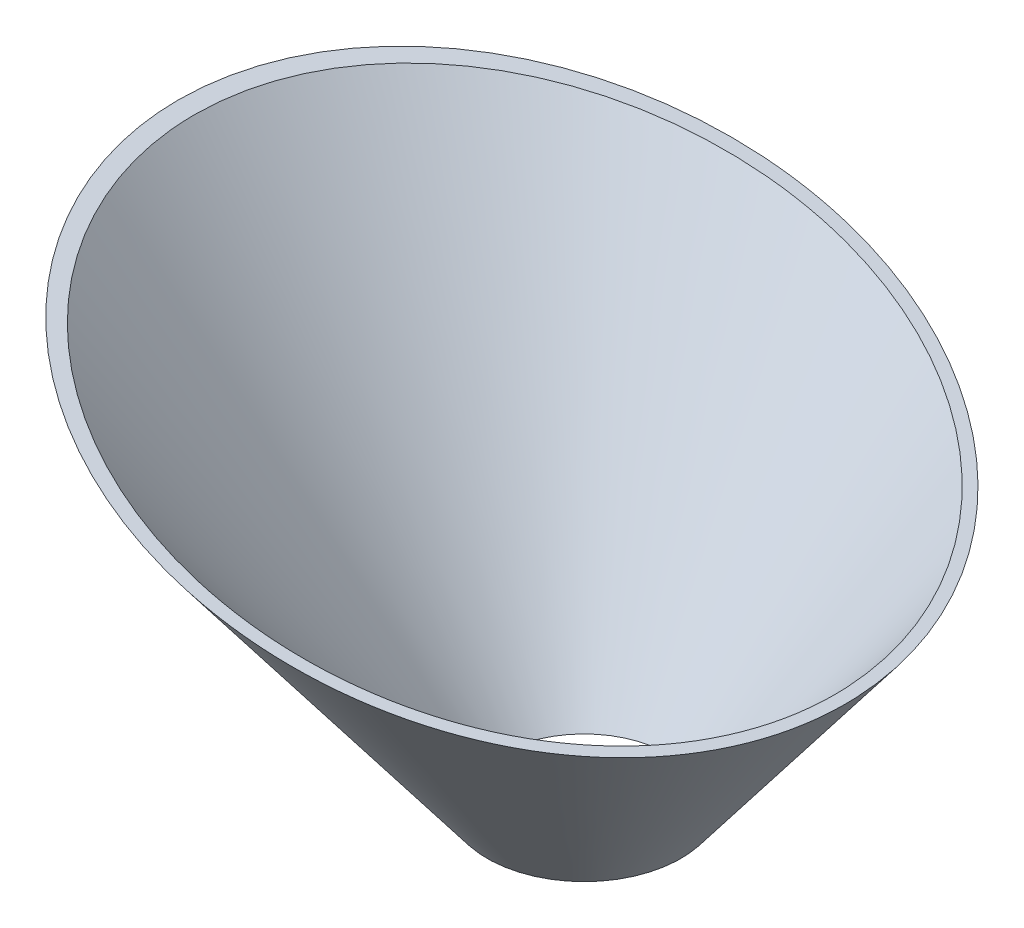
SolidWorks part; units mm, degrees
ref_plane "Front Plane" through (0, 0, 0) normal (0, 0, 1) x (1, 0, 0)
ref_plane "Top Plane" through (0, 0, 0) normal (0, 1, 0) x (1, 0, 0)
ref_plane "Right Plane" through (0, 0, 0) normal (1, 0, 0) x (0, 0, -1)
sketch "Sketch3" plane through (0, 0, 0) normal (0, 0, 1) x (1, 0, 0)
  line L0 (0, 0) -> (-24.257, 0)
  line L1 (-24.257, 0) -> (-101.6, 101.6)
  line L2 (-101.6, 101.6) -> (0, 101.6)
  line L3 (0, 0) -> (0, 101.6)
  dimension "D1" = 24.257
  dimension "D2" = 101.6
  dimension "D3" = 101.6
revolve "Revolve1" add sketch "Sketch3" angle 360 about L3
shell "Shell1" thickness 2.54
sketch "Sketch4" plane through (0, 0, 0) normal (0, 0, 1) x (1, 0, 0)
  line L0 (0, 0) -> (0, 101.6) construction
  line L1 (0, 0) -> (24.257, 0) construction
  line L3 (101.6, 101.6) -> (0, 101.6)
  line L5 (24.257, 0) -> (65.4416, 54.1012) construction
  line L6 (65.4416, 54.1012) -> (101.6, 101.6)
  line L7 (24.257, 0) -> (101.6, 101.6) construction
  line L8 (0, 0) -> (-24.257, 0) construction
  line L9 (-24.257, 0) -> (-101.6, 101.6) construction
  line L10 (-101.6, 101.6) -> (0, 101.6)
  line L11 (65.4416, 54.1012) -> (-101.6, 101.6)
  dimension "D1" = 101.6
  dimension "D2" = 101.6
  dimension "D3" = 24.257
extrude "Cut-Extrude4" cut sketch "Sketch4" against normal through all and the other way through all
equation "\"Foamcore\" = .1in"
equation "\"MDF\" = .3in"
equation "\"Gmaterial\"= \"MDF\""
equation "\"PVC-ID\" = \"1.590in\""
equation "\"PVC-OD\" = \"1.900in\""
equation "\"PVC-Sleeve-Width\" = \".51in\""
